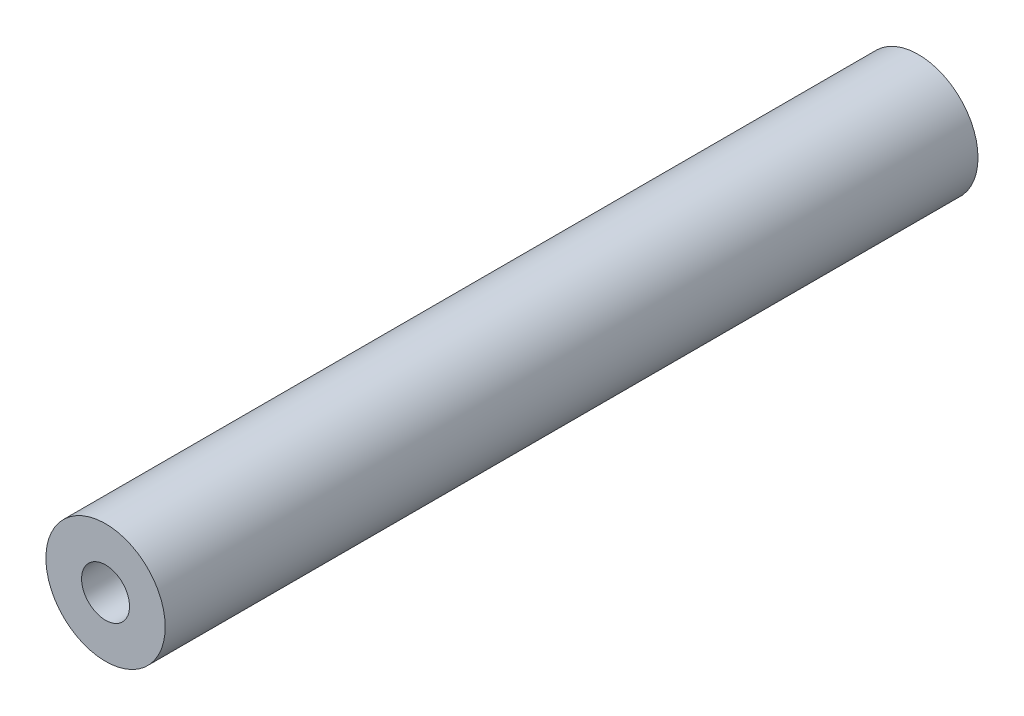
SolidWorks part; units mm, degrees
ref_plane "Front Plane" through (0, 0, 0) normal (0, 0, 1) x (1, 0, 0)
ref_plane "Top Plane" through (0, 0, 0) normal (0, 1, 0) x (1, 0, 0)
ref_plane "Right Plane" through (0, 0, 0) normal (1, 0, 0) x (0, 0, -1)
sketch "Sketch1" plane through (0, 0, 0) normal (0, 0, 1) x (1, 0, 0)
  circle A0 centre (0, 0) radius 6.35
  dimension "D1" = 12.7
extrude "Boss-Extrude1" add sketch "Sketch1" along normal mid plane 86.5167
sketch "Sketch2" plane through (0, 0, 43.2583) normal (0, 0, 1) x (1, 0, 0)
  point P0 (0, 0)
  point P1 (0, 0)
hole_wizard "Tap Drill for 1/4-20 Tap1" positions "Sketch4" profile "Sketch3" hole size "1/4-20" standard "ANSI Inch"
sketch "Sketch4" plane through (0, 0, 43.2583) normal (0, 0, 1) x (1, 0, 0)
  point P0 (0, 0)
sketch "Sketch3" plane through (0, 0, 43.2583) normal (1, 0, 0) x (0, -1, 0)
  line L0 (0, 0) -> (0, 17.4088)
  line L1 (0, 17.4088) -> (2.5527, 15.875)
  line L2 (2.5527, 15.875) -> (2.5527, 0)
  line L5 (2.5527, 0) -> (0, 0)
  line L10 (0, 17.4088) -> (-2.5527, 15.875) construction
  line L11 (0, -6.35) -> (0, 107.95) construction
  dimension "Hole Dia." = 5.1054
  dimension "Hole Depth" = 15.875
  dimension "Drill Angle" = 118
mirror "Mirror1" about plane through (0, 0, 0) normal (0, 0, 1) of "Tap Drill for 1/4-20 Tap1"
